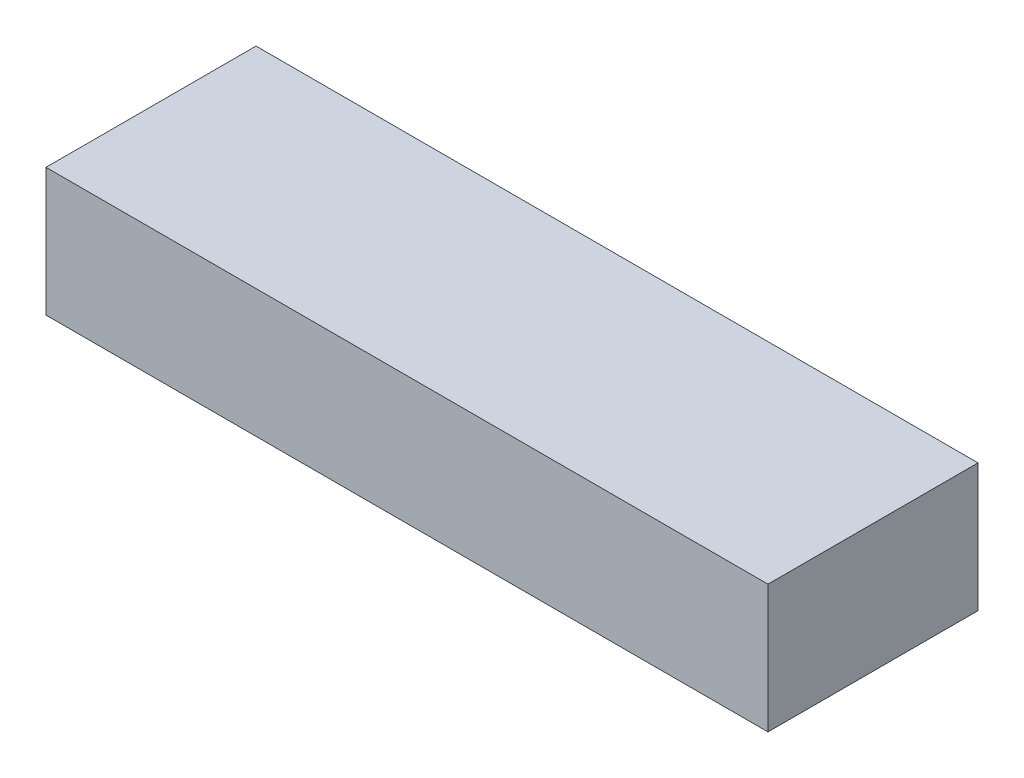
SolidWorks part; units mm, degrees
material "Nickel silver 65-12, UNS C75700"
ref_plane "Front Plane" through (0, 0, 0) normal (0, 0, 1) x (1, 0, 0)
ref_plane "Top Plane" through (0, 0, 0) normal (0, 1, 0) x (1, 0, 0)
ref_plane "Right Plane" through (0, 0, 0) normal (1, 0, 0) x (0, 0, -1)
sketch "Sketch1" plane through (0, 0, 0) normal (0, 1, 0) x (1, 0, 0)
  line L1 (0, 0) -> (22, 0)
  line L2 (0, 0) -> (0, 6.4)
  line L3 (0, 6.4) -> (22, 6.4)
  line L4 (22, 0) -> (22, 6.4)
  dimension "D1" = 22
  dimension "D2" = 6.4
extrude "Boss-Extrude1" add sketch "Sketch1" along normal blind 3.9
